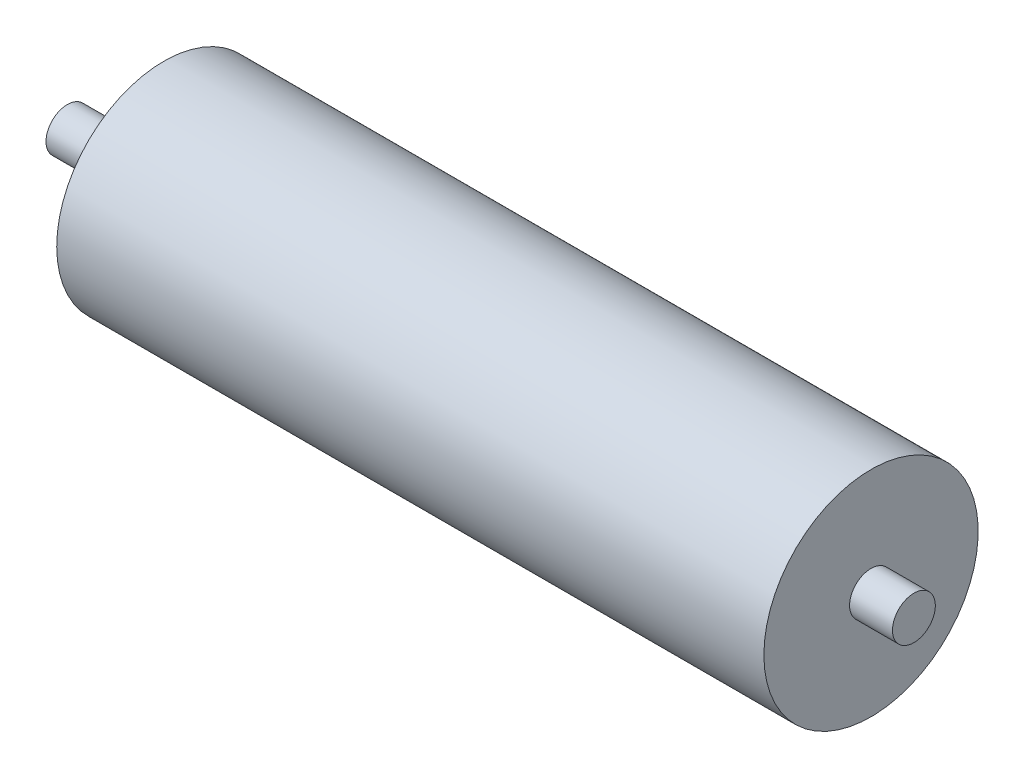
SolidWorks part; units mm, degrees
ref_plane "Front Plane" through (0, 0, 0) normal (0, 0, 1) x (1, 0, 0)
ref_plane "Top Plane" through (0, 0, 0) normal (0, 1, 0) x (1, 0, 0)
ref_plane "Right Plane" through (0, 0, 0) normal (1, 0, 0) x (0, 0, -1)
sketch "Sketch1" plane through (0, 0, 0) normal (0, 0, 1) x (1, 0, 0)
  line L0 (-200.0651, 0) -> (194.9349, 0) construction
  line L1 (-200.0651, 0) -> (-200.0651, 10)
  line L2 (-200.0651, 10) -> (-155.0651, 10)
  line L3 (-155.0651, 10) -> (-155.0651, 50)
  line L4 (-155.0651, 50) -> (174.9349, 50)
  line L9 (174.9349, 50) -> (174.9349, 10)
  line L10 (174.9349, 10) -> (194.9349, 10)
  line L11 (194.9349, 10) -> (194.9349, 0)
  line L12 (-200.0651, 0) -> (194.9349, 0)
  point P3 (0, 0)
  point P8 (69.031, 58.759)
  point P9 (71.824, 60)
  dimension "D1" = 395
  dimension "D2" = 50
  dimension "D5" = 10
  dimension "D6" = 45
  dimension "D7" = 20
revolve "Revolve1" add sketch "Sketch1" angle 360 about L0
